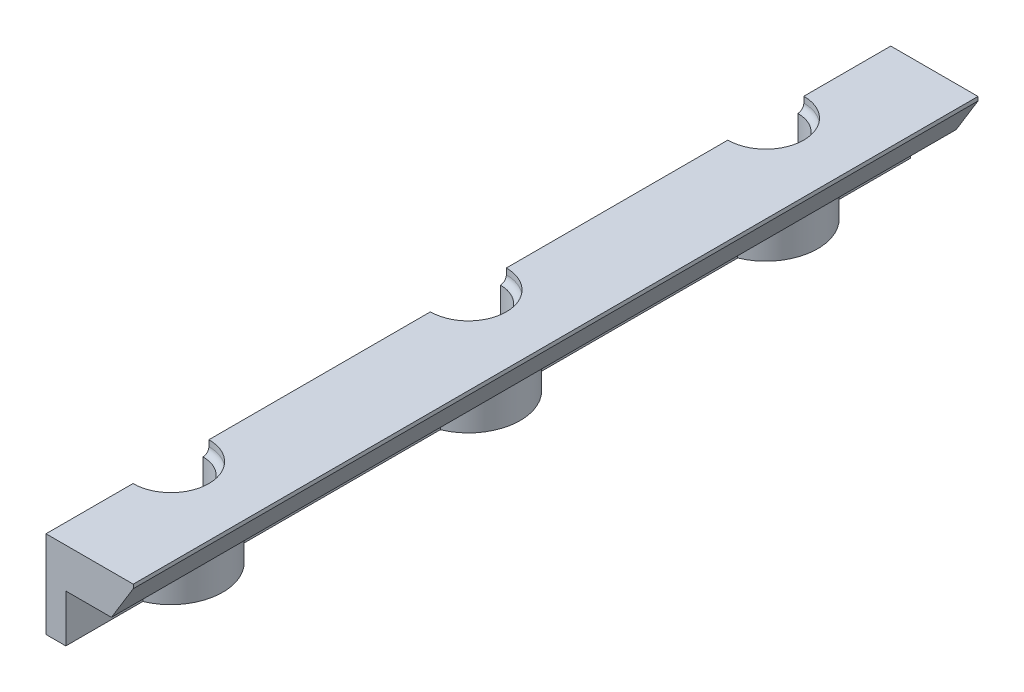
SolidWorks part; units mm, degrees
ref_plane "Płaszczyzna przednia" through (0, 0, 0) normal (0, 0, 1) x (1, 0, 0)
ref_plane "Płaszczyzna górna" through (0, 0, 0) normal (0, 1, 0) x (1, 0, 0)
ref_plane "Płaszczyzna prawa" through (0, 0, 0) normal (1, 0, 0) x (0, 0, -1)
sketch "Sketch1" plane through (0, 0, 0) normal (0, 1, 0) x (1, 0, 0)
  line L0 (0, 65.8555) -> (0, -65.8555) construction
  line L1 (0, -8.075) -> (0, -31.5)
  line L2 (0, -31.5) -> (22, -31.5)
  line L3 (104.3478, 75) -> (-104.3478, 75) construction
  line L4 (22, -31.5) -> (22, 181.5)
  line L5 (0, 158.075) -> (0, 181.5)
  line L6 (0, 181.5) -> (22, 181.5)
  line L7 (0, 8.075) -> (0, 66.925)
  line L8 (0, 83.075) -> (0, 141.925)
  arc A6 (0, -8.075) -> (0, 8.075) centre (0, 0) ccw
  arc A7 (0, 66.925) -> (0, 83.075) centre (0, 75) ccw
  arc A8 (0, 141.925) -> (0, 158.075) centre (0, 150) ccw
  point P7 (0, 0)
  point P20 (0, 75)
  point P23 (22, 75)
  dimension "D1" = 31.5
  dimension "D2" = 16.15
  dimension "D3" = 75
  dimension "D6" = 3
  dimension "D5" = 22
extrude "Boss-Extrude1" add sketch "Sketch1" against normal blind 10
sketch "Sketch3" plane through (0, -10, 0) normal (0, -1, 0) x (1, 0, 0)
  line L23 (0, -181.5) -> (0, -158.075)
  line L24 (0, -141.925) -> (0, -83.075)
  line L25 (0, -66.925) -> (0, -8.075)
  line L26 (0, 8.075) -> (0, 31.5)
  line L27 (5, -181.5) -> (5, -162.0812)
  line L28 (5, -137.9188) -> (5, -87.0812)
  line L29 (5, -62.9188) -> (5, -12.0812)
  line L30 (5, 12.0812) -> (5, 31.5)
  line L31 (5, -181.5) -> (5, -162.0812)
  line L32 (5, -137.9188) -> (5, -87.0812)
  line L33 (5, -62.9188) -> (5, -12.0812)
  line L34 (5, 12.0812) -> (5, 31.5)
  line L35 (0, 31.5) -> (5, 31.5)
  line L36 (0, -181.5) -> (5, -181.5)
  arc A15 (0, -158.075) -> (0, -141.925) centre (0, -150) ccw
  arc A16 (0, -83.075) -> (0, -66.925) centre (0, -75) ccw
  arc A17 (0, -8.075) -> (0, 8.075) centre (0, 0) ccw
  arc A18 (5, -162.0812) -> (5, -137.9188) centre (0, -150) ccw
  arc A19 (5, -87.0812) -> (5, -62.9188) centre (0, -75) ccw
  arc A20 (5, -12.0812) -> (5, 12.0812) centre (0, 0) ccw
  arc A21 (5, -162.0812) -> (5, -137.9188) centre (0, -150) ccw
  arc A22 (5, -87.0812) -> (5, -62.9188) centre (0, -75) ccw
  arc A23 (5, -12.0812) -> (5, 12.0812) centre (0, 0) ccw
  dimension "D1" = 5
extrude "Boss-Extrude2" add sketch "Sketch3" along normal blind 12
sketch "Sketch7" plane through (0, 0, 0) normal (-1, 0, 0) x (0, 0, 1)
  line L0 (-158.075, 0) -> (-171.075, 0) construction
  line L1 (-181.5, 0) -> (-158.075, 0) construction
  line L2 (-171.075, 0) -> (-171.075, -22) construction
  line L3 (-158.075, -22) -> (-181.5, -22) construction
  line L4 (-171.075, -11) -> (-158.075, -11) construction
  line L5 (-158.075, -22) -> (-158.075, 0) construction
  line L7 (-150, 0) -> (-150, -22) construction
  line L8 (-141.925, 0) -> (-158.075, 0) construction
  line L9 (-158.075, -22) -> (-141.925, -22) construction
  circle A0 centre (-170.5, -4) radius 1.95
  circle A1 centre (-170.5, -18) radius 1.95
  circle A2 centre (-129.5, -4) radius 1.95
  circle A3 centre (-129.5, -18) radius 1.95
  circle A4 centre (-95.5, -4) radius 1.95
  circle A5 centre (-54.5, -4) radius 1.95
  circle A6 centre (-54.5, -18) radius 1.95
  circle A7 centre (-95.5, -18) radius 1.95
  circle A8 centre (-20.5, -4) radius 1.95
  circle A9 centre (20.5, -4) radius 1.95
  circle A10 centre (20.5, -18) radius 1.95
  circle A11 centre (-20.5, -18) radius 1.95
  dimension "D2" = 3.9
  dimension "D3" = 4
  dimension "D4" = 3
  dimension "D1" = 13
extrude "Cut-Extrude3" cut sketch "Sketch7" against normal blind 14 and the other way blind 6
sketch "Sketch8" plane through (0, 0, 0) normal (-1, 0, 0) x (0, 0, 1)
  line L0 (-83.075, -22) -> (-141.925, -22) construction
  line L1 (-141.925, 0) -> (-112.5, -18.5) construction
  line L2 (-112.5, -18.5) -> (-83.075, 0) construction
  circle A0 centre (-112.5, -18.5) radius 1.95
  dimension "D1" = 3.9
  dimension "D2" = 3.5
extrude "Cut-Extrude4" cut sketch "Sketch8" against normal blind 4 contours A0
sketch "Sketch9" plane through (4, 0, 0) normal (-1, 0, 0) x (0, 0, 1)
  circle A0 centre (-112.5, -18.5) radius 1.5
  circle A1 centre (-112.5, -18.5) radius 1.95 construction
  dimension "D1" = 3
extrude "Cut-Extrude5" cut sketch "Sketch9" against normal blind 4
pattern_linear "LPattern1" count 2 spacing 75 along (0, 0, 1) of "Cut-Extrude4", "Cut-Extrude5"
chamfer "Chamfer2" distance 5.5 distance2 9 1 edges at (22, -10, -75)
ref_plane "Plane1" through (0, 0, -75) normal (0, 0, 1) x (1, 0, 0)
chamfer "Chamfer3" distance 7 distance2 2 3 edges at (8.075, -22, 0) (8.075, -22, -75) (8.075, -22, -150)
sketch "Sketch10" plane through (0, 0, 0) normal (-1, 0, 0) x (0, 0, 1)
  line L3 (-158.075, -15) -> (-158.075, 0) construction
  line L4 (-181.5, 0) -> (-158.075, 0) construction
  line L5 (-159.575, 1.5818) -> (-159.575, -1.5)
  line L6 (-159.575, 1.5818) -> (-158.075, 0)
  line L7 (-150, 2.1978) -> (-150, -6.9976) construction
  line L8 (-150, 2.1978) -> (-158.075, 0) construction
  line L9 (-150, 2.1978) -> (-141.925, 0) construction
  arc A0 (-159.575, -1.5) -> (-158.075, 0) centre (-158.075, -1.5) ccw
  dimension "D1" = 3
revolve "Cut-Revolve1" cut sketch "Sketch10" angle 360 about L7
pattern_linear "LPattern2" count 3 spacing 75 along (0, 0, 1) of "Cut-Revolve1"
